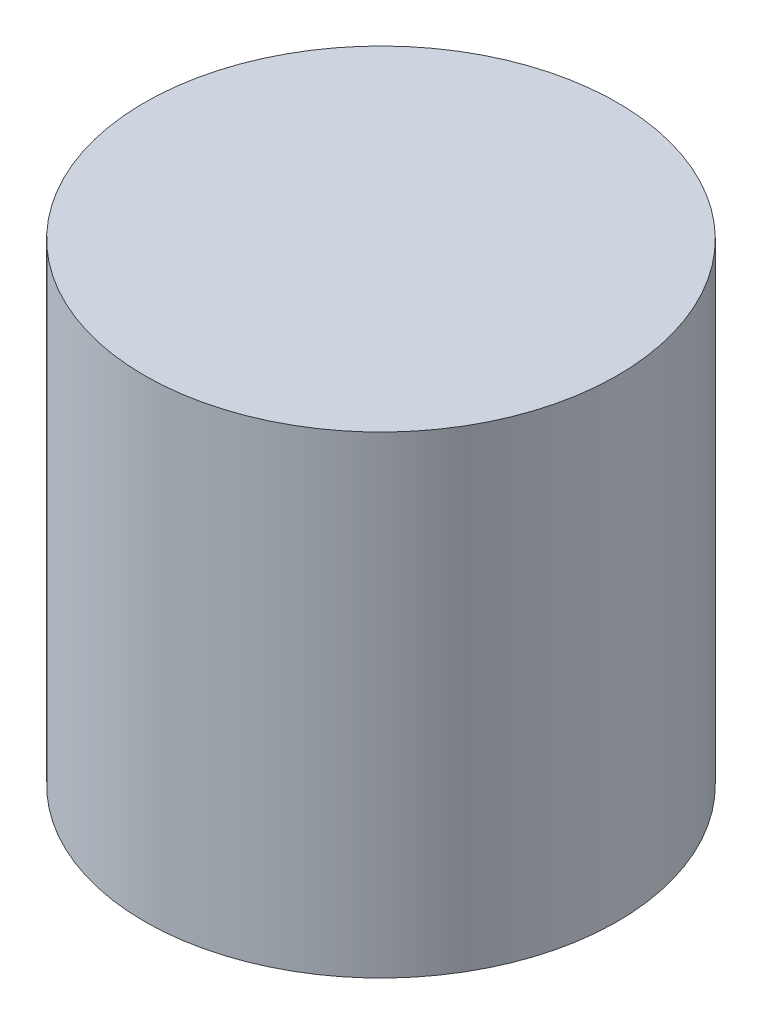
SolidWorks part; units mm, degrees
ref_plane "Front Plane" through (0, 0, 0) normal (0, 0, 1) x (1, 0, 0)
ref_plane "Top Plane" through (0, 0, 0) normal (0, 1, 0) x (1, 0, 0)
ref_plane "Right Plane" through (0, 0, 0) normal (1, 0, 0) x (0, 0, -1)
sketch "Sketch1" plane through (0, 0, 0) normal (0, 1, 0) x (1, 0, 0)
  circle A0 centre (0, 0) radius 250
  dimension "D1" = 500
extrude "Boss-Extrude1" add sketch "Sketch1" along normal blind 500
